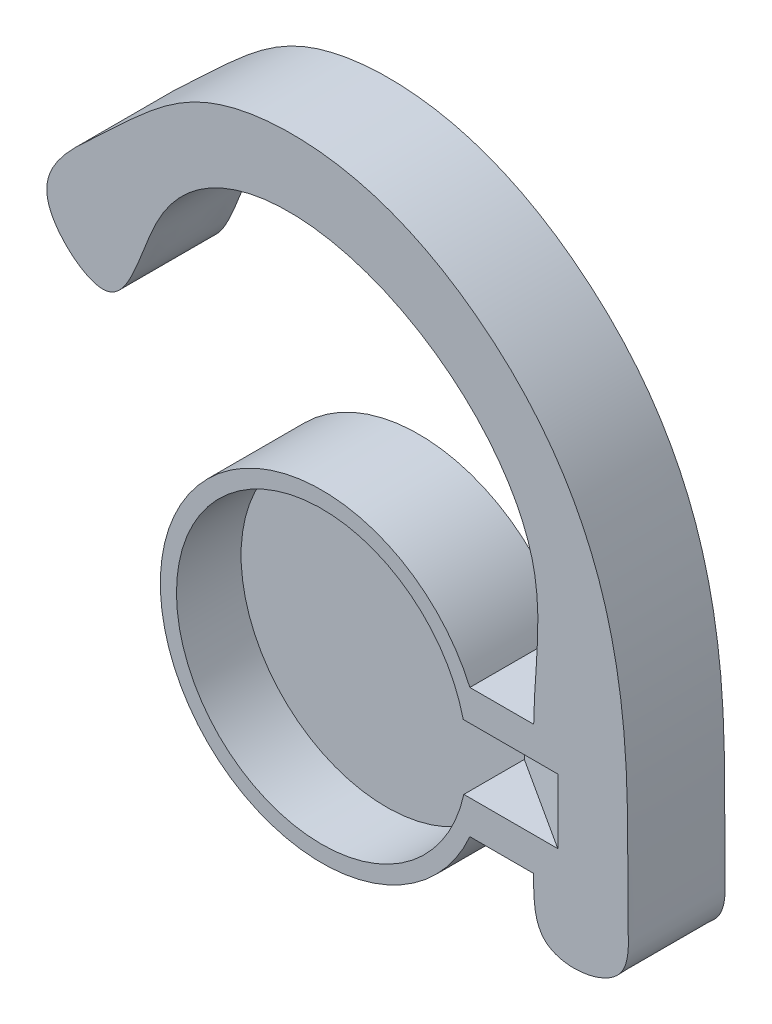
SolidWorks part; units mm, degrees
ref_plane "Front Plane" through (0, 0, 0) normal (0, 0, 1) x (1, 0, 0)
ref_plane "Top Plane" through (0, 0, 0) normal (0, 1, 0) x (1, 0, 0)
ref_plane "Right Plane" through (0, 0, 0) normal (1, 0, 0) x (0, 0, -1)
sketch "Sketch2" plane through (0, 0, 0) normal (0, 0, 1) x (1, 0, 0)
  line L1 (14.5497, 6.35) -> (20.8253, 6.35)
  line L2 (14.5497, -6.35) -> (20.8253, -6.35)
  arc A0 (14.5497, 6.35) -> (14.5497, -6.35) centre (0, 0) ccw
  spline S0 degree 3 poles (20.8253, 6.35) (20.8494, 10.8011) (23.7372, 25.6451) (2.0917, 41.9581) (-16.7781, 34.7488) (-19.3517, 18.6424) (-29.9945, 27.9195) (-20.433, 36.2459) (-12.3444, 44.6869) (2.9918, 45.3612) (14.431, 39.596) (22.5119, 31.7132) (27.8079, 22.0641) (30.3548, 8.8212) (29.9788, -1.8435) (30.2821, -12.1696) (20.6571, -13.5416) (20.8218, -8.15) (20.8253, -6.35) knots 0.002766 0.002766 0.002766 0.002766 0.067804 0.213762 0.286377 0.336463 0.371585 0.416644 0.481576 0.551683 0.618604 0.665651 0.71459 0.777516 0.857861 0.878753 0.915074 0.940872 0.940872 0.940872 0.940872
  dimension "D1" = 31.75
  dimension "D4" = 198.1195
  dimension "D5" = 55.65
  dimension "D2" = 12.7
  dimension "D3" = 6.2756
extrude "Boss-Extrude1" add sketch "Sketch2" along normal blind 9.525
sketch "Sketch3" plane through (0, 0, 9.525) normal (0, 0, 1) x (1, 0, 0)
  circle A0 centre (0, 0) radius 14.2875
  dimension "D1" = 28.575
extrude "Cut-Extrude1" cut sketch "Sketch3" against normal blind 6.35
sketch "Sketch4" plane through (0, 0, 9.525) normal (0, 0, 1) x (1, 0, 0)
  line L0 (13.4704, 4.7625) -> (13.4704, -4.7625)
  line L1 (13.4704, 4.7625) -> (19.8204, 4.7625)
  line L2 (13.4704, -4.7625) -> (19.8204, -4.7625)
  line L3 (19.8204, 4.7625) -> (19.8204, -4.7625)
  circle A0 centre (0, 0) radius 14.2875 construction
  dimension "D1" = 9.525
  dimension "D2" = 6.35
sketch "Sketch5" plane through (0, -6.35, 0) normal (0, -1, 0) x (1, 0, 0)
  line L0 (13.3393, 3.175) -> (25.9513, 11.3022)
  line L7 (-15.875, 0) -> (14.5497, 0) construction
  line L8 (13.3393, 3.175) -> (13.3393, 11.3022)
  line L9 (13.3393, 11.3022) -> (25.9513, 11.3022)
  point P1 (25.9513, 11.3022)
  point P6 (27.8574, 11.3314)
  dimension "D1" = 3.175
extrude "Cut-Extrude3" cut sketch "Sketch5" against normal blind 6.35 from offset 3.302
